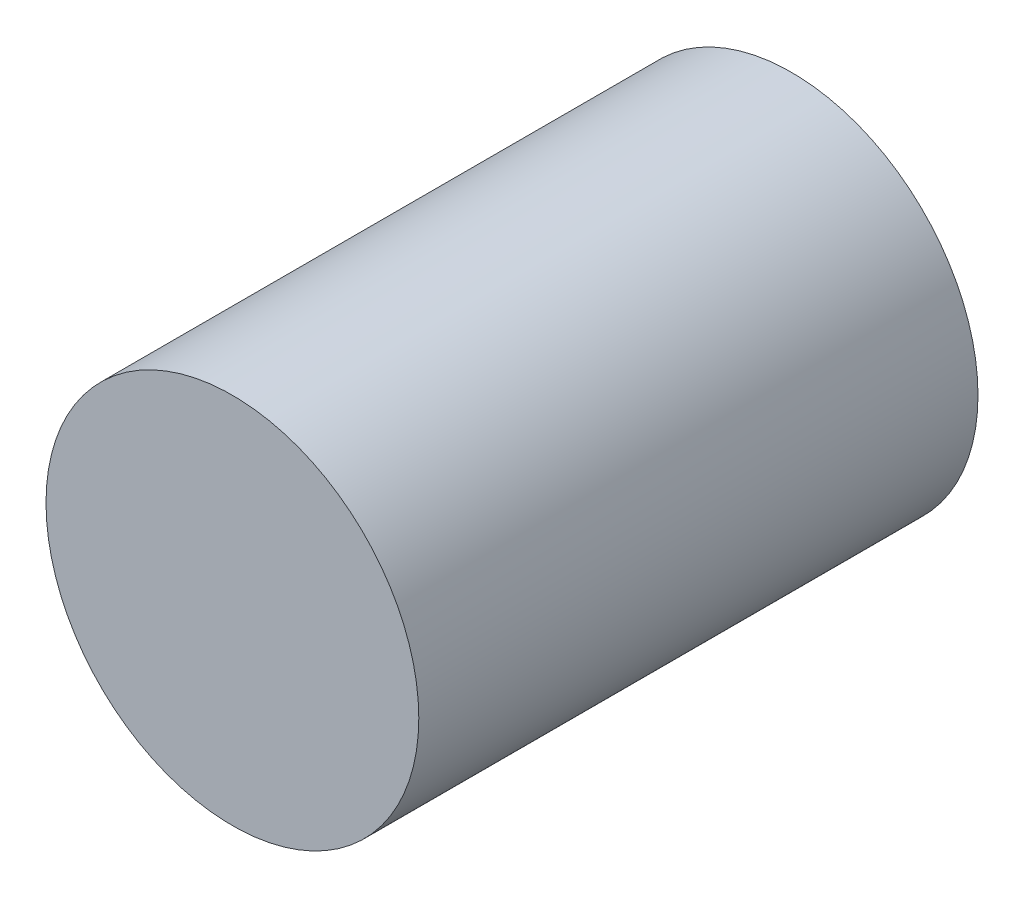
SolidWorks part; units mm, degrees
ref_plane "Front Plane" through (0, 0, 0) normal (0, 0, 1) x (1, 0, 0)
ref_plane "Top Plane" through (0, 0, 0) normal (0, 1, 0) x (1, 0, 0)
ref_plane "Right Plane" through (0, 0, 0) normal (1, 0, 0) x (0, 0, -1)
sketch "Sketch2" plane through (0, 0, 0) normal (0, 0, 1) x (1, 0, 0)
  circle A0 centre (0, 0) radius 10
  dimension "D1" = 20
extrude "Boss-Extrude2" add sketch "Sketch2" along normal blind 30
